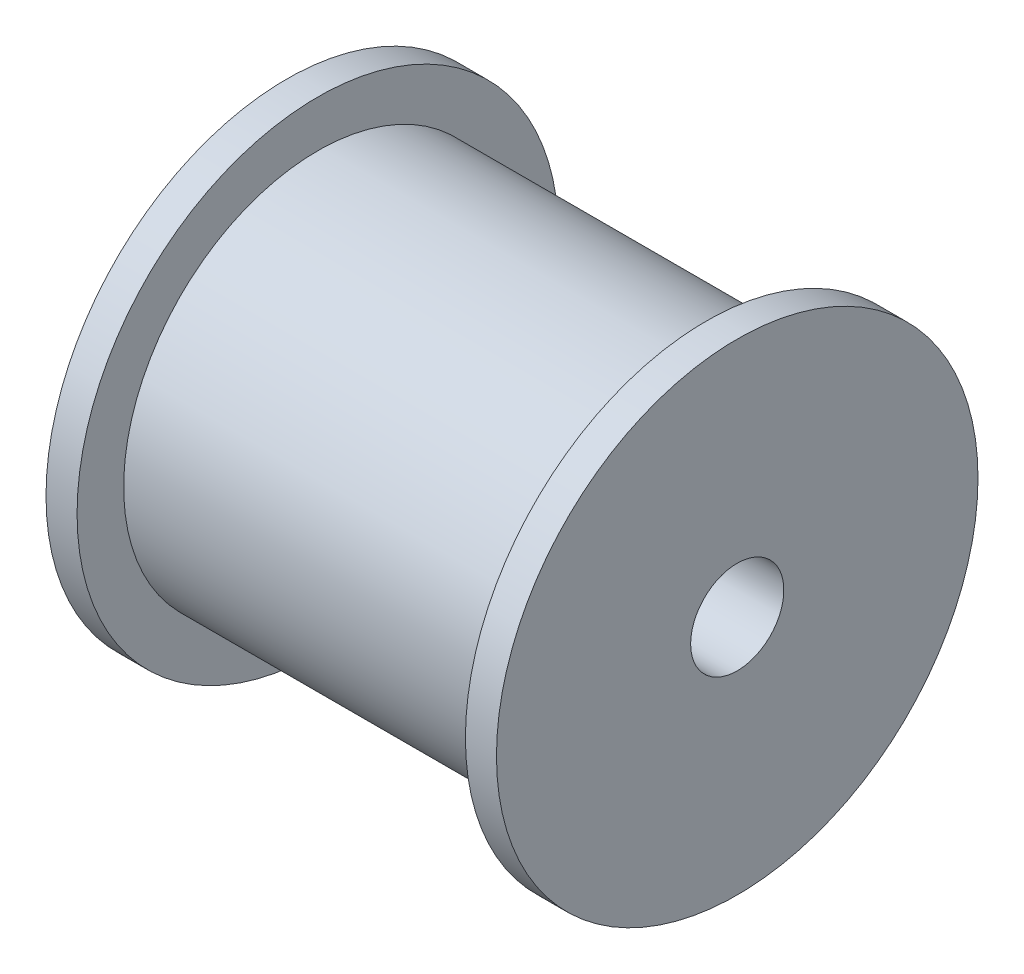
SolidWorks part; units mm, degrees
ref_plane "Front Plane" through (0, 0, 0) normal (0, 0, 1) x (1, 0, 0)
ref_plane "Top Plane" through (0, 0, 0) normal (0, 1, 0) x (1, 0, 0)
ref_plane "Right Plane" through (0, 0, 0) normal (1, 0, 0) x (0, 0, -1)
sketch "Sketch1" plane through (0, 0, 0) normal (1, 0, 0) x (0, 0, -1)
  circle A0 centre (0, 0) radius 125
  dimension "D2" = 250
extrude "Boss-Extrude1" add sketch "Sketch1" along normal blind 250
sketch "Sketch2" plane through (0, 0, 0) normal (1, 0, 0) x (0, 0, -1)
  circle A0 centre (0, 0) radius 125 construction
  circle A1 centre (0, 0) radius 125 construction
  circle A2 centre (0, 0) radius 155
  dimension "D1" = 30
extrude "Boss-Extrude2" add sketch "Sketch2" against normal blind 20
ref_plane "Plane1" through (125, 0, 0) normal (1, 0, 0) x (0, 0, -1)
mirror "Mirror1" about plane through (125, 0, 0) normal (1, 0, 0) of "Boss-Extrude2"
sketch "Sketch3" plane through (-20, 0, 0) normal (-1, 0, 0) x (0, 0, 1)
  circle A0 centre (0, 0) radius 30
  dimension "D1" = 60
extrude "Cut-Extrude1" cut sketch "Sketch3" against normal through all
